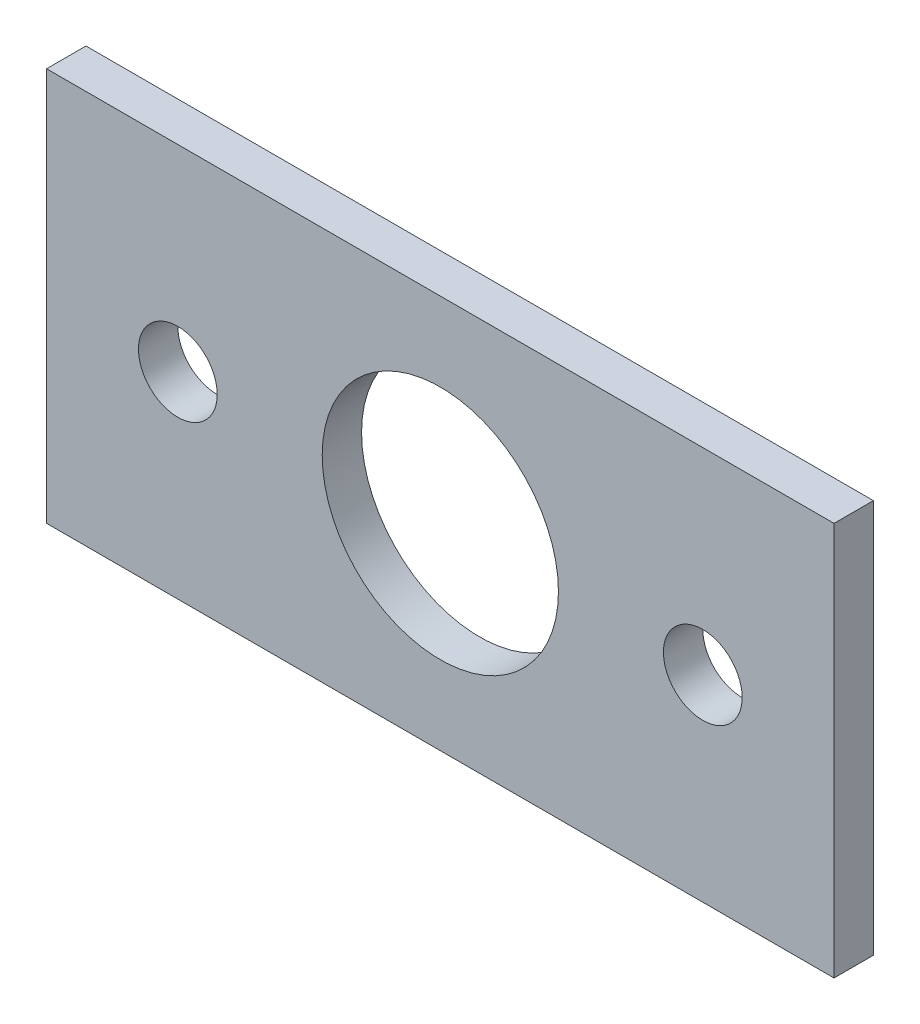
SolidWorks part; units mm, degrees
ref_plane "Plan de face" through (0, 0, 0) normal (0, 0, 1) x (1, 0, 0)
ref_plane "Plan de dessus" through (0, 0, 0) normal (0, 1, 0) x (1, 0, 0)
ref_plane "Plan de droite" through (0, 0, 0) normal (1, 0, 0) x (0, 0, -1)
sketch "Esquisse1" plane through (0, 0, 0) normal (0, 0, 1) x (1, 0, 0)
  line L0 (-26.8631, 5.6819) -> (3.1369, 5.6819) construction
  line L1 (-26.8631, 13.1819) -> (3.1369, 13.1819)
  line L2 (-26.8631, 13.1819) -> (-26.8631, -1.8181)
  line L3 (-26.8631, -1.8181) -> (3.1369, -1.8181)
  line L4 (3.1369, 13.1819) -> (3.1369, -1.8181)
  circle A0 centre (-11.8631, 5.6819) radius 4.5
  circle A1 centre (-21.8631, 5.6819) radius 1.5
  circle A2 centre (-1.8631, 5.6819) radius 1.5
  dimension "D3" = 5
  dimension "D1" = 15
  dimension "D2" = 30
  dimension "D4" = 5
extrude "Extrusion1" add sketch "Esquisse1" along normal blind 1.5
